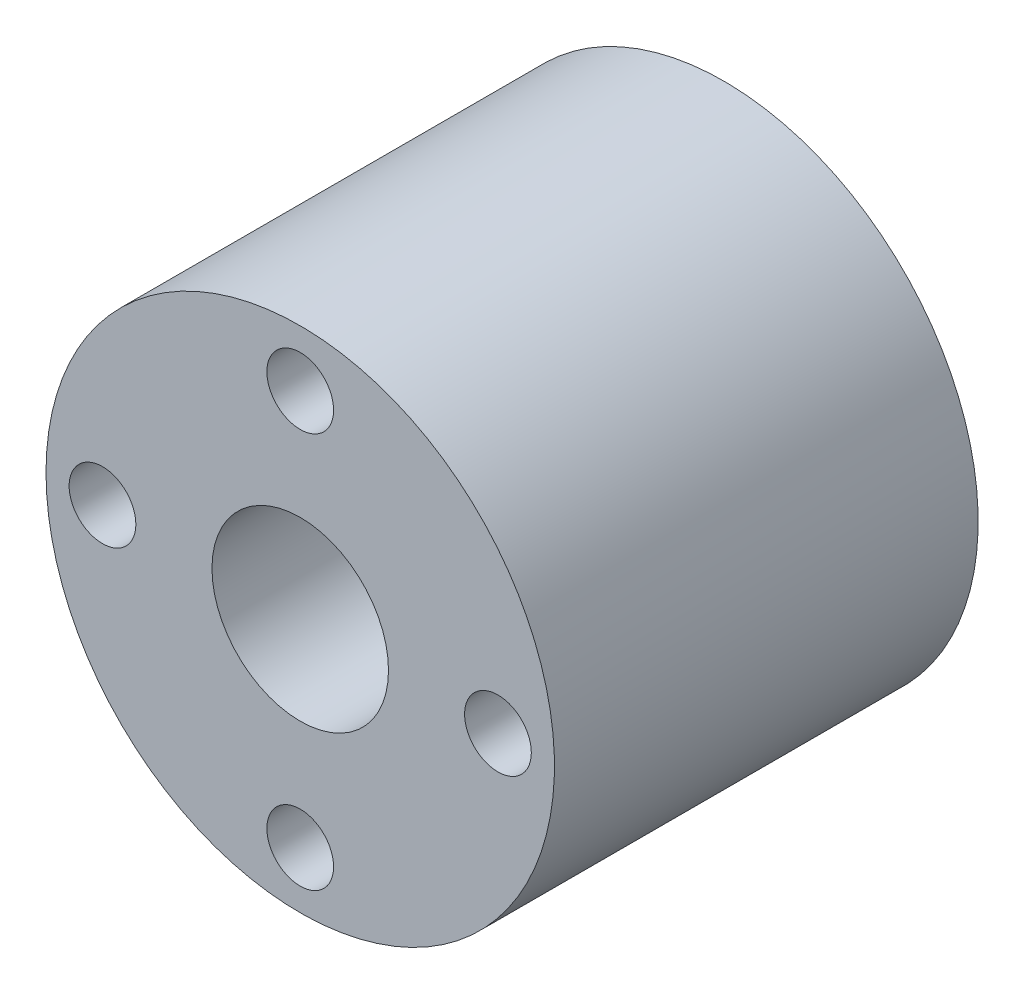
SolidWorks part; units mm, degrees
ref_plane "Front Plane" through (0, 0, 0) normal (0, 0, 1) x (1, 0, 0)
ref_plane "Top Plane" through (0, 0, 0) normal (0, 1, 0) x (1, 0, 0)
ref_plane "Right Plane" through (0, 0, 0) normal (1, 0, 0) x (0, 0, -1)
sketch "Sketch1" plane through (0, 0, 0) normal (0, 0, 1) x (1, 0, 0)
  circle A0 centre (0, 0) radius 11.43
  circle A1 centre (0, 0) radius 3.9688
extrude "Boss-Extrude1" add sketch "Sketch1" along normal blind 19.05
sketch "Sketch4" plane through (0, 0, 19.05) normal (0, 0, 1) x (1, 0, 0)
  line L0 (0, -55) -> (0, 55) construction
  point P0 (0, 8.89)
  point P4 (0, 0)
hole_wizard "Ø3.0mm Dowel Hole1" positions "Sketch4" profile "Sketch5" hole size "Ø3.0" standard "ANSI Metric" end condition through all
sketch "Sketch5" plane through (0, 8.89, 19.05) normal (1, 0, 0) x (0, -1, 0)
  line L0 (0, 0) -> (0, 19.05)
  line L1 (0, 19.05) -> (1.5, 19.05)
  line L2 (1.5, 19.05) -> (1.5, 0)
  line L5 (1.5, 0) -> (0, 0)
  line L11 (0, -6.35) -> (0, 107.95) construction
  dimension "Thru Hole Dia." = 3
  dimension "Thru Hole Depth" = 19.05
pattern_circular "CirPattern1" count 4 over 360 about axis through (0, 0, 0) along (0, 0, 1) of "Ø3.0mm Dowel Hole1"
